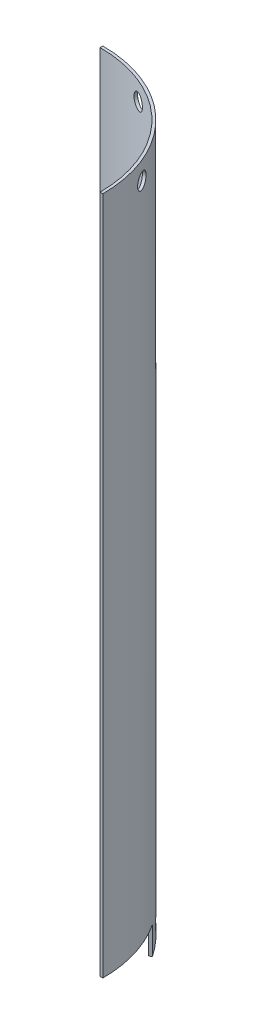
SolidWorks part; units mm, degrees
material "1060 Alloy"
ref_plane "Front Plane" through (0, 0, 0) normal (0, 0, 1) x (1, 0, 0)
ref_plane "Top Plane" through (0, 0, 0) normal (0, 1, 0) x (1, 0, 0)
ref_plane "Right Plane" through (0, 0, 0) normal (1, 0, 0) x (0, 0, -1)
sketch "Sketch1" plane through (0, 0, 0) normal (0, 1, 0) x (1, 0, 0)
  line L0 (0, 0) -> (0, 92)
  line L1 (0, 0) -> (92, 0)
  circle A0 centre (0, 0) radius 90
  circle A1 centre (0, 0) radius 92
  dimension "Internal Diameter" = 180
  dimension "External Diameter" = 184
extrude "Boss-Extrude1" add sketch "Sketch1" along normal blind 508.5 contours L1 A1 L0 A0
ref_plane "Plane1" through (0, 10, 0) normal (0, -1, 0) x (-1, 0, 0)
sketch "Sketch2" plane through (0, 10, 0) normal (0, -1, 0) x (-1, 0, 0)
  line L0 (0, 0) -> (-84.9969, 35.2069)
  line L1 (0, 0) -> (-65.0538, 65.0538)
  line L2 (0, 0) -> (-92, 0) construction
  line L3 (0, 0) -> (-35.2069, 84.9969)
  arc A0 (0, 92) -> (-92, 0) centre (0, 0) ccw construction
  dimension "D1" = 135
  dimension "D2" = 22.5
ref_plane "Plane2" through (84.9969, 0, -35.2069) normal (0.9239, 0, -0.3827) x (-0.3827, 0, -0.9239)
ref_plane "Plane3" through (35.2069, 0, -84.9969) normal (0.3827, 0, -0.9239) x (-0.9239, 0, -0.3827)
sketch "Sketch3" plane through (84.9969, 0, -35.2069) normal (0.9239, 0, -0.3827) x (-0.3827, 0, -0.9239)
  circle A0 centre (0, 10) radius 5.565
  point P0 (0, 10)
  dimension "Left Hole Diameter" = 11.13
sketch "Sketch5" plane through (35.2069, 0, -84.9969) normal (0.3827, 0, -0.9239) x (-0.9239, 0, -0.3827)
  line L0 (0, 10) -> (-84.9969, 10) construction
  circle A0 centre (0, 10) radius 5.565
  dimension "Right Hole Diameter" = 11.13
ref_plane "Plane4" through (65.0538, 0, -65.0538) normal (0.7071, 0, -0.7071) x (-0.7071, 0, -0.7071)
sketch "Sketch6" plane through (65.0538, 0, -65.0538) normal (0.7071, 0, -0.7071) x (-0.7071, 0, -0.7071)
  line L0 (0, 10) -> (-65.0538, 10) construction
  line L1 (0, 10) -> (35.2069, 10) construction
  circle A0 centre (0, 10) radius 5.565
  dimension "Middle Hole Diameter" = 11.13
extrude "Cut-Extrude4" cut sketch "Sketch6" against normal up to surface (2.1722 mm away)
extrude "Cut-Extrude2" cut sketch "Sketch3" against normal up to surface (2.1722 mm away) contours A0
extrude "Cut-Extrude3" cut sketch "Sketch5" against normal up to surface (2.1722 mm away) contours A0
pattern_linear "LPattern2" count 2 spacing 485.5 along (0, 1, 0) of "Cut-Extrude2", "Cut-Extrude3"
sketch "Sketch7" plane through (0, 0, 0) normal (0, -1, 0) x (1, 0, 0)
  line L0 (0, 0) -> (65.0538, -65.0538) construction
  line L1 (0.3118, -0.3118) -> (57.9282, -0.3118) construction
  line L2 (0.3118, -0.3118) -> (76.4474, -51.184)
  line L3 (0.3118, -0.3118) -> (51.184, -76.4474)
  line L6 (92, 0) -> (90, 0)
  line L7 (0, -90) -> (0, -92)
  line L8 (92, 0) -> (90, 0)
  line L9 (0, -90) -> (0, -92)
  arc A0 (0, -92) -> (92, 0) centre (0, 0) ccw construction
  arc A2 (0, -90) -> (90, 0) centre (0, 0) ccw
  arc A3 (0, -92) -> (92, 0) centre (0, 0) ccw
  arc A4 (0, -90) -> (90, 0) centre (0, 0) ccw
  arc A5 (0, -92) -> (92, 0) centre (0, 0) ccw
  line M4 (92, 0) -> (90, 0)
  arc M5 (90, 0) -> (0, -90) centre (0, 0) cw
  line M6 (0, -90) -> (0, -92)
  arc M7 (0, -92) -> (92, 0) centre (0, 0) ccw
  dimension "D1" = 45
  dimension "D2" = 11.25
  dimension "D3" = 0
extrude "Cut-Extrude5" cut sketch "Sketch7" against normal blind 20 contours L2 M5 M7 M4 | L3 M5 M6 M7 | A4 L8 A5 L9
equation "\"Total Panel Length\"= 508.5"
equation "\"Internal Panel Diameter\"= 180"
equation "\"External Panel Diameter\"= 184"
equation "\"L & R Mounting Hole Diameter\" = 11.13"
equation "\"M Mounting Hole DIameter\"= 11.13"
equation "\"Mounting Hole Dist. from Top\" = 13"
equation "\"Mounting Hole Dist. from Base\" = 10"
equation "\"External Diameter@Sketch1\"= \"External Panel Diameter\""
equation "\"Internal Diameter@Sketch1\"= \"Internal Panel Diameter\""
equation "\"Panel Length@Boss-Extrude1\"= \"Total Panel Length\""
equation "\"Left Hole Diameter@Sketch3\" = \"L & R Mounting Hole Diameter\""
equation "\"Right Hole Diameter@Sketch5\" = \"L & R Mounting Hole Diameter\""
equation "\"Middle Hole Diameter@Sketch6\" = \"M Mounting Hole DIameter\""
equation "\"Mounting from Base@Plane1\" = \"Mounting Hole Dist. from Base\""
equation "\"Mounting from Top@LPattern2\"= \"Total Panel Length\" - \"Mounting Hole Dist. from Base\" - \"Mounting Hole Dist. from Top\""
equation "\"Base Tab Length@Cut-Extrude5\" = \"Base Tab Length\""
equation "\"Base Tab Length\"= 20"
